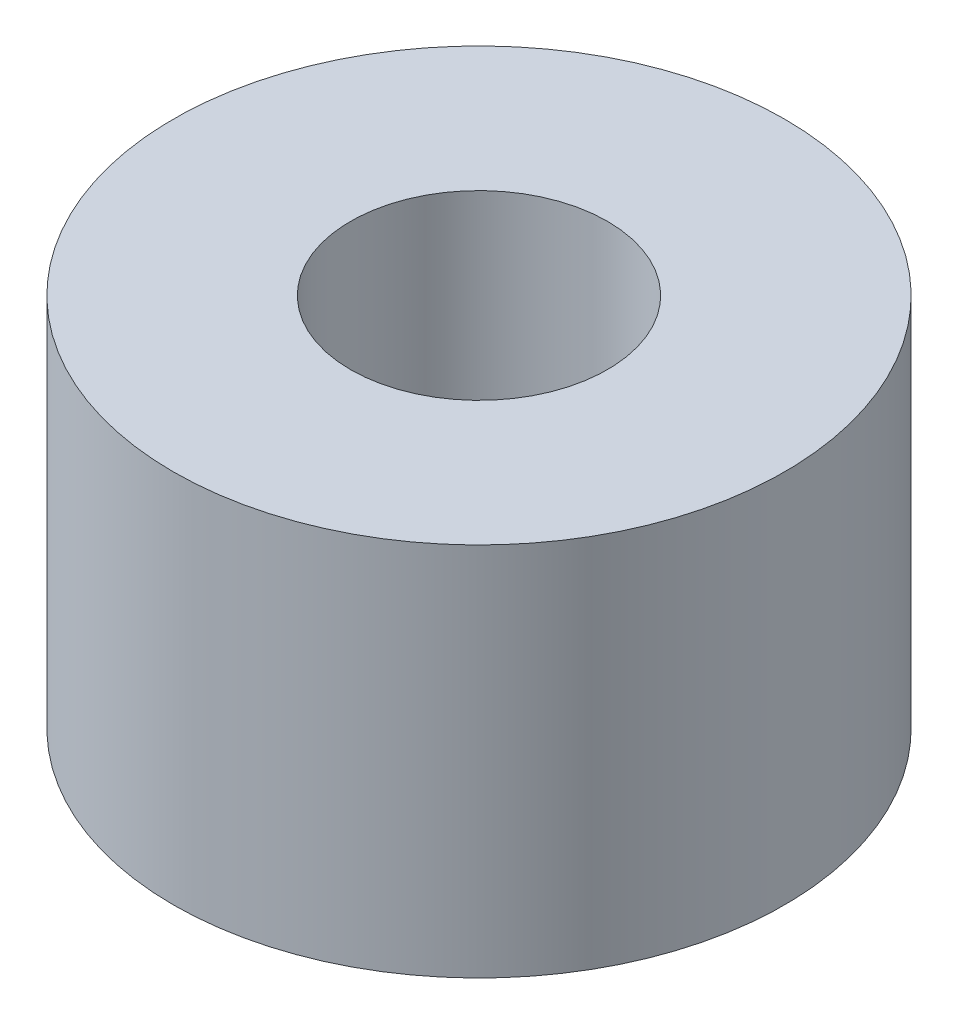
SolidWorks part; units mm, degrees
ref_plane "Front Plane" through (0, 0, 0) normal (0, 0, 1) x (1, 0, 0)
ref_plane "Top Plane" through (0, 0, 0) normal (0, 1, 0) x (1, 0, 0)
ref_plane "Right Plane" through (0, 0, 0) normal (1, 0, 0) x (0, 0, -1)
sketch "Sketch1" plane through (0, 0, 0) normal (0, 1, 0) x (1, 0, 0)
  circle A0 centre (0, 0) radius 23.495
  circle A1 centre (0, 0) radius 55.88
  arc A2 (55.7237, 4.176) -> (54.5932, 11.923) centre (0, 0) ccw construction
  arc A3 (21.8709, 8.5837) -> (20.6044, 11.2903) centre (0, 0) ccw construction
extrude "Boss-Extrude1" add sketch "Sketch1" along normal blind 68.58
